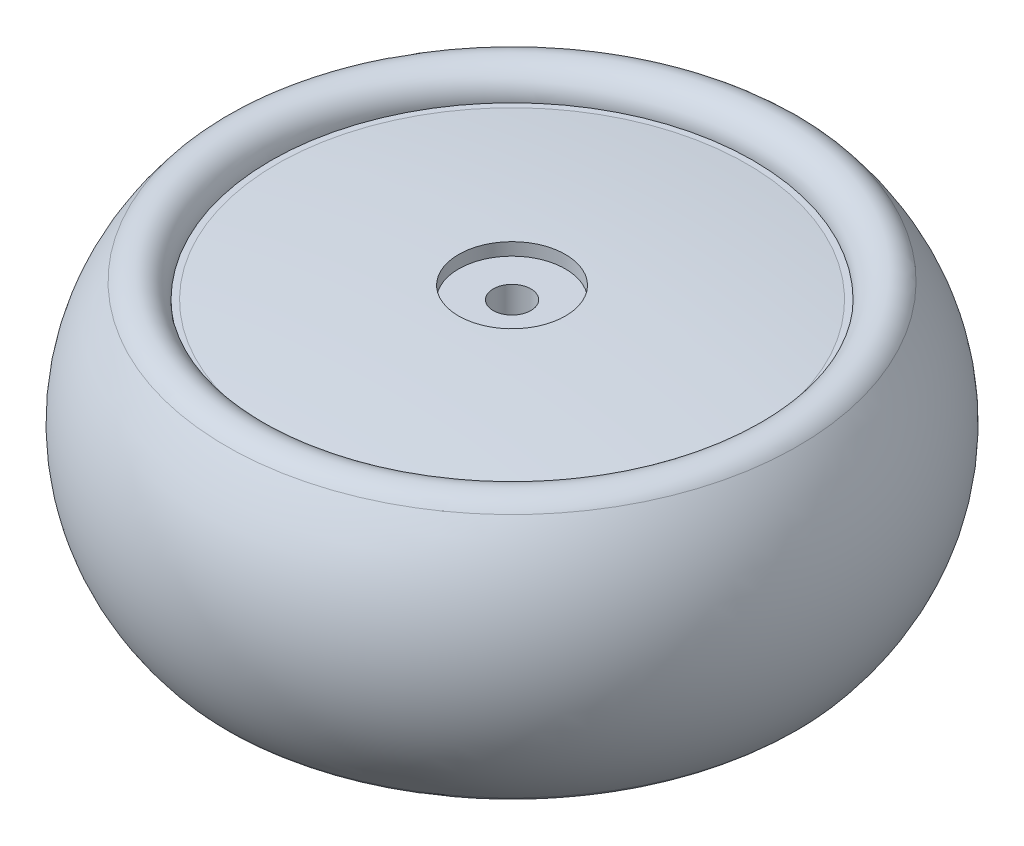
SolidWorks part; units mm, degrees
ref_plane "Front Plane" through (0, 0, 0) normal (0, 0, 1) x (1, 0, 0)
ref_plane "Top Plane" through (0, 0, 0) normal (0, 1, 0) x (1, 0, 0)
ref_plane "Right Plane" through (0, 0, 0) normal (1, 0, 0) x (0, 0, -1)
sketch "Sketch1" plane through (0, 0, 0) normal (1, 0, 0) x (0, 0, -1)
  line L0 (0, 88.3569) -> (0, -74.4581) construction
  line L1 (2.3813, 26.9875) -> (2.3813, 22.225)
  line L2 (2.3813, 22.225) -> (26.67, 22.225)
  line L3 (26.67, 22.225) -> (26.67, 0)
  line L4 (26.67, 0) -> (30.48, 0)
  line L5 (30.48, 0) -> (30.48, 26.9875)
  line L6 (2.3813, 26.9875) -> (6.7469, 26.9875)
  line L7 (6.7469, 28.575) -> (6.7469, 26.9875)
  line L8 (30.48, 26.9875) -> (29.718, 26.9875)
  line L9 (-30.48, 26.9875) -> (-29.718, 26.9875) construction
  line L10 (-6.7469, 28.575) -> (-6.7469, 26.9875) construction
  line L11 (-2.3812, 26.9875) -> (-6.7469, 26.9875) construction
  line L12 (-30.48, 0) -> (-30.48, 26.9875) construction
  line L13 (-26.67, 0) -> (-30.48, 0) construction
  line L14 (-26.67, 22.225) -> (-26.67, 0) construction
  line L15 (-2.3812, 22.225) -> (-26.67, 22.225) construction
  line L16 (-2.3812, 26.9875) -> (-2.3812, 22.225) construction
  arc A0 (6.7469, 28.575) -> (29.718, 26.9875) centre (0.9943, -221.6547) cw
  dimension "D10" = 250.2958
  dimension "D1" = 26.9875
  dimension "D2" = 22.225
  dimension "D3" = 0.762
  dimension "D4" = 1.5875
  dimension "D5" = 60.96
  dimension "D6" = 4.7625
  dimension "D7" = 13.4937
  dimension "D8" = 3.81
  dimension "D9" = 28.575
revolve "Revolve1" add sketch "Sketch1" angle 360 about L0
sketch "Sketch2" plane through (0, 0, 0) normal (0, 0, 1) x (1, 0, 0)
  line L0 (0, -2.6228) -> (0, 35.2563) construction
  line L1 (-41.656, 30.1625) -> (-41.656, -3.175) construction
  line L2 (30.48, 26.9875) -> (-30.48, 26.9875) construction
  line L3 (-30.48, 0) -> (30.48, 0) construction
  line L4 (-30.48, 26.9875) -> (-30.48, 0) construction
  line L5 (-23.8831, 26.9875) -> (-41.656, 26.9875) construction
  line L6 (-22.4723, 0) -> (-41.656, 0) construction
  line L7 (-30.48, -13.5078) -> (-30.48, 41.7726) construction
  line L8 (-30.48, 26.9875) -> (-30.48, 0)
  arc A0 (-30.48, 26.9875) -> (-36.1099, 29.001) centre (-33.655, 26.9875) ccw
  arc A1 (-30.48, 0) -> (-36.1099, -2.0135) centre (-33.655, 0) cw
  arc A2 (-36.1099, 29.001) -> (-36.1099, -2.0135) centre (-17.2034, 13.4938) ccw
  dimension "D4" = 3.175
  dimension "D5" = 3.175
  dimension "D1" = 3.175
  dimension "D2" = 3.175
  dimension "D3" = 11.176
revolve "Revolve2" add sketch "Sketch2" angle 360 about L0
